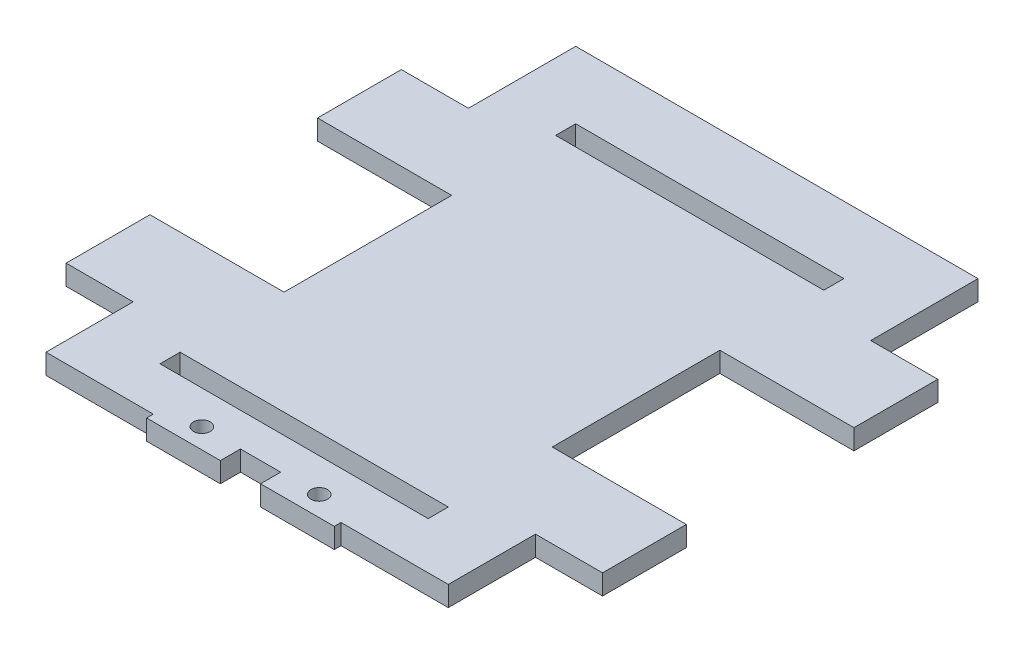
SolidWorks part; units mm, degrees
ref_plane "Front Plane" through (0, 0, 0) normal (0, 0, 1) x (1, 0, 0)
ref_plane "Top Plane" through (0, 0, 0) normal (0, 1, 0) x (1, 0, 0)
ref_plane "Right Plane" through (0, 0, 0) normal (1, 0, 0) x (0, 0, -1)
sketch "Sketch1" plane through (0, 0, 0) normal (0, 1, 0) x (1, 0, 0)
  line L0 (0, 25) -> (80, 25)
  line L1 (0, 0) -> (80, 0)
  line L2 (0, 0) -> (0, 50)
  line L3 (0, 50) -> (80, 50)
  line L4 (80, 0) -> (80, 50)
  line L5 (10, 0) -> (70, 0)
  line L6 (10, 0) -> (10, -16)
  line L7 (10, -16) -> (70, -16)
  line L8 (70, 0) -> (70, -16)
  line L9 (20, -3) -> (60, -3)
  line L10 (20, -3) -> (20, -6)
  line L11 (20, -6) -> (60, -6)
  line L12 (60, -3) -> (60, -6)
  line L13 (20, 53) -> (20, 56)
  line L14 (60, 53) -> (60, 56)
  line L15 (20, 53) -> (60, 53)
  line L16 (20, 56) -> (60, 56)
  line L17 (70, 50) -> (70, 66)
  line L18 (10, 66) -> (70, 66)
  line L19 (10, 50) -> (10, 66)
  line L20 (0, 50) -> (80, 50)
  line L21 (0, 50) -> (0, 25)
  line L22 (0, 37.5) -> (20, 37.5)
  line L23 (20, 37.5) -> (20, 12.5)
  line L24 (20, 25) -> (60, 25)
  line L25 (60, 12.5) -> (60, 37.5)
  line L26 (60, 37.5) -> (80, 37.5)
  line L27 (60, 12.5) -> (80, 12.5)
  line L28 (0, 12.5) -> (20, 12.5)
  point P13 (40, -3)
  point P14 (40, 0)
  dimension "D1" = 80
  dimension "D2" = 50
  dimension "D3" = 10
  dimension "D4" = 10
  dimension "D5" = 16
  dimension "D6" = 3
  dimension "D7" = 3
  dimension "D8" = 40
  dimension "D9" = 0
extrude "Boss-Extrude1" add sketch "Sketch1" along normal blind 3 contours L1 L4 L3 L2 | L8 L1 L6 L7 L9 L12 L11 L10 | L19 L3 L17 L18 L13 L16 L14 L15 | L25 L26 L4 L3 L21 L22 L23 L0
sketch "Sketch2" plane through (0, 0, 0) normal (0, 1, 0) x (1, 0, 0)
  line L0 (40, -16) -> (40, -6)
  line L1 (10, -16) -> (70, -16) construction
  line L2 (20, -6) -> (60, -6) construction
  line L3 (40, -11) -> (31.25, -11)
  circle A0 centre (31.25, -11) radius 1.25
  circle A1 centre (48.75, -11) radius 1.25
  dimension "D2" = 2.5
  dimension "D1" = 8.75
extrude "Cut-Extrude1" cut sketch "Sketch2" along normal blind 10
sketch "Sketch3" plane through (0, 0, 0) normal (0, 1, 0) x (1, 0, 0)
  line L0 (40, -16) -> (40, -6)
  line L1 (10, -16) -> (70, -16) construction
  line L2 (20, -6) -> (60, -6) construction
  line L3 (10, -13) -> (26, -13)
  line L4 (10, 0) -> (10, -16) construction
  line L5 (26, -13) -> (26, -16)
  line L6 (26, -13) -> (26, -13.9996)
  line L7 (37, -16) -> (37, -11)
  line L8 (37, -11) -> (43, -11)
  line L9 (10, -13) -> (10, -16)
  line L10 (10, -16) -> (26, -16)
  line L11 (37, -16) -> (43, -16)
  line L12 (43, -16) -> (43, -11)
  line L13 (54, -13) -> (54, -16)
  line L14 (70, -13) -> (70, -16)
  line L15 (70, -16) -> (54, -16)
  line L16 (70, -13) -> (54, -13)
  line L17 (26, -13.9996) -> (37, -13.9996)
  line L18 (37, -13.9996) -> (37, -16)
  line L19 (26, -16) -> (37, -16)
  line L20 (26, -16) -> (37, -16)
  line L21 (54, -16) -> (43, -16)
  line L22 (54, -13.9996) -> (43, -13.9996)
  point P18 (40, -11)
  dimension "D1" = 16
  dimension "D2" = 3
  dimension "D3" = 3
  dimension "D4" = 5
extrude "Cut-Extrude2" cut sketch "Sketch3" along normal blind 10 contours L9 L10 L5 L3 | L7 L11 L0 L8 | L11 L12 L8 L0 | L14 L16 L13 L15 | L5 L19 L7 L17 | L13 L22 L12 L21
